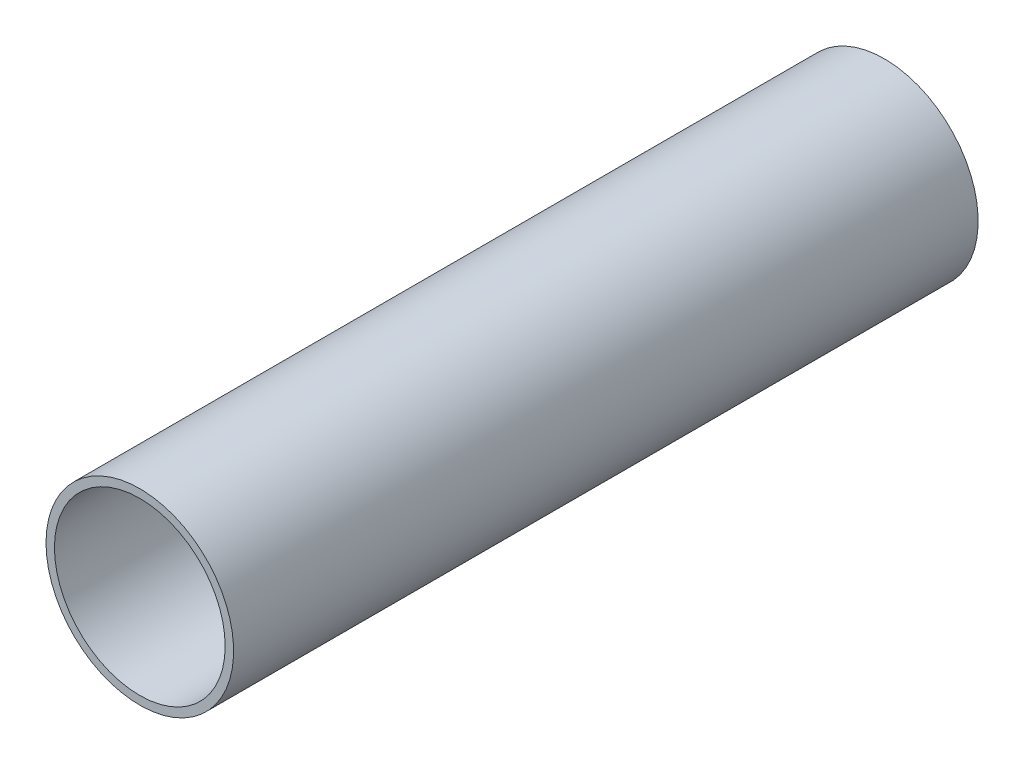
SolidWorks part; units mm, degrees
material "E-Glass Fiber"
ref_plane "Front Plane" through (0, 0, 0) normal (0, 0, 1) x (1, 0, 0)
ref_plane "Top Plane" through (0, 0, 0) normal (0, 1, 0) x (1, 0, 0)
ref_plane "Right Plane" through (0, 0, 0) normal (1, 0, 0) x (0, 0, -1)
sketch "Sketch1" plane through (0, 0, 0) normal (0, 0, 1) x (1, 0, 0)
  circle A0 centre (0, 0) radius 19.2
  circle A1 centre (0, 0) radius 17.475
  dimension "D1" = 38.4
  dimension "D2" = 34.95
extrude "Boss-Extrude1" add sketch "Sketch1" along normal blind 152.4
